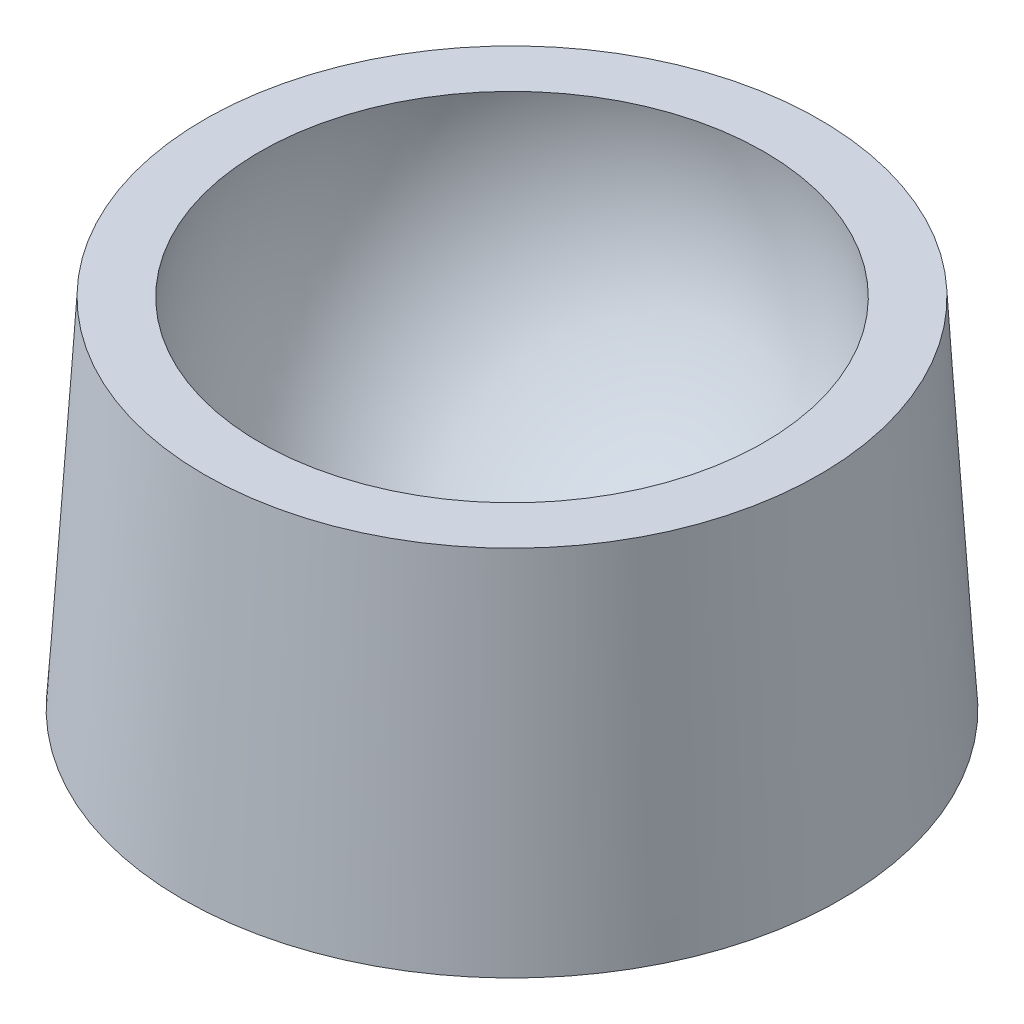
SolidWorks part; units mm, degrees
material "A286 Demir Tabanlı Süperalaşım"
ref_plane "Ön Düzlem" through (0, 0, 0) normal (0, 0, 1) x (1, 0, 0)
ref_plane "Üst Düzlem" through (0, 0, 0) normal (0, 1, 0) x (1, 0, 0)
ref_plane "Sağ Düzlem" through (0, 0, 0) normal (1, 0, 0) x (0, 0, -1)
sketch "Çizim1" plane through (0, 0, 0) normal (1, 0, 0) x (0, 0, -1)
  line L0 (0, 1.4985) -> (0, 0)
  line L2 (1.2488, 0) -> (4.8687, 0)
  line L3 (6.993, 0.999) -> (11.8387, 0.999)
  line L4 (12.8962, 1.2843) -> (12.0583, 14.985)
  line L5 (12.0583, 14.985) -> (9.877, 14.985)
  line L6 (2.997, 3.2498) -> (2.997, 1.4985)
  line L7 (2.997, 1.4985) -> (1.2488, 1.4985)
  line L8 (11.8387, 0.999) -> (12.9137, 0.999)
  line L9 (0, 0) -> (1.2488, 0)
  line L10 (12.8962, 1.2843) -> (12.9137, 0.999)
  line L11 (1.2488, 1.4985) -> (0, 1.4985)
  arc A0 (4.8687, 0) -> (6.993, 0.999) centre (0, 13.1112) ccw
  arc A1 (3.6327, 4.1804) -> (9.877, 14.985) centre (0, 13.4865) ccw
  arc A2 (3.6327, 4.1804) -> (2.997, 3.2498) centre (3.996, 3.2498) ccw
revolve "Döndür3" add sketch "Çizim1" angle 360 about L0
sketch "Çizim2" plane through (0, 0, 0) normal (0, -1, 0) x (1, 0, 0)
  circle A0 centre (0, 0) radius 1.25
extrude "Kes-Ekstrüzyon1" cut sketch "Çizim2" against normal blind 10
